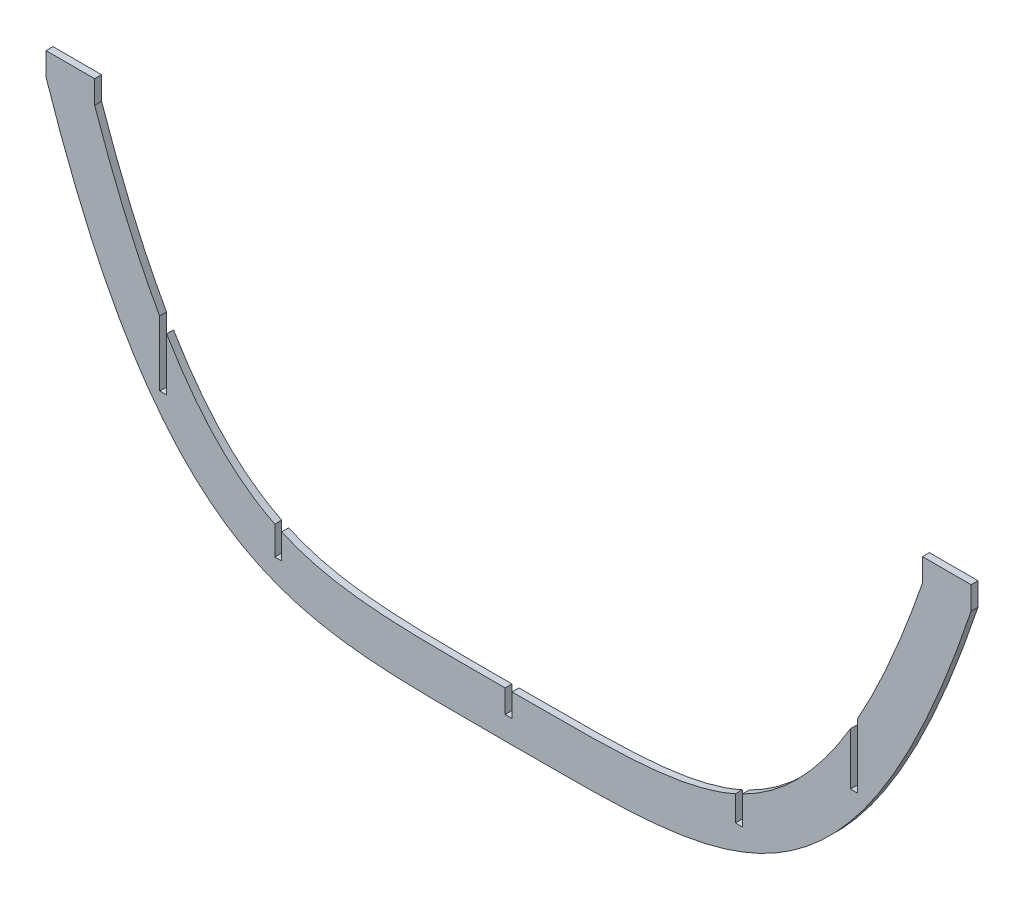
SolidWorks part; units mm, degrees
ref_plane "Front Plane" through (0, 0, 0) normal (0, 0, 1) x (1, 0, 0)
ref_plane "Top Plane" through (0, 0, 0) normal (0, 1, 0) x (1, 0, 0)
ref_plane "Right Plane" through (0, 0, 0) normal (1, 0, 0) x (0, 0, -1)
sketch "Sketch1" plane through (0, 0, 0) normal (0, 0, 1) x (1, 0, 0)
  line L4 (-200.8571, 150) -> (-200.8571, 160)
  line L5 (-200.8571, 160) -> (-179.7305, 160)
  line L6 (-179.7305, 160) -> (-179.7305, 150)
  line L7 (200.8571, 150) -> (200.8571, 160)
  line L8 (200.8571, 160) -> (179.7305, 160)
  line L9 (179.7305, 160) -> (179.7305, 150)
  spline S0 degree 4 poles (-216.8089, 203.6342) (-108.4044, -203.6342) (0, 203.6342) (108.4044, -203.6342) (216.8089, 203.6342) knots 0 0 0 0 0 1 1 1 1 1 construction
  spline S1 degree 4 poles (-200.8571, 150) (-100.4286, -150) (0, 150) (100.4286, -150) (200.8571, 150) knots 0.036788 0.036788 0.036788 0.036788 0.036788 0.963212 0.963212 0.963212 0.963212 0.963212
  spline S2 degree 1 poles (-181.8916, 156.3489) (181.8916, 156.3489) knots 0 0 1 1 construction
  spline S3 degree 3 poles (-181.8916, 156.3489) (-181.3891, 154.848) (-180.3653, 151.8253) (-178.3412, 145.9898) (-175.81, 138.9489) (-172.7858, 130.9351) (-168.7678, 120.7983) (-163.7768, 109.1306) (-157.8474, 96.6329) (-151.9892, 85.5414) (-144.2887, 72.4973) (-134.9007, 59.2193) (-124.0868, 47.3263) (-113.706, 38.6442) (-103.5943, 32.3808) (-93.4771, 27.8904) (-83.0914, 24.7263) (-68.685, 21.8783) (-49.5164, 20.3042) (-25.1066, 19.9753) (0, 20.0124) (25.1066, 19.9753) (49.5164, 20.3042) (68.685, 21.8783) (83.0914, 24.7263) (93.4771, 27.8904) (103.5943, 32.3808) (113.706, 38.6442) (124.0868, 47.3263) (134.9007, 59.2193) (144.2887, 72.4973) (151.9892, 85.5414) (157.8474, 96.6329) (163.7768, 109.1306) (168.7678, 120.7983) (172.7858, 130.9351) (175.81, 138.9489) (178.3412, 145.9898) (180.3653, 151.8253) (181.3891, 154.848) (181.8916, 156.3489) knots 0.036788 0.036788 0.036788 0.036788 0.040406 0.044025 0.051263 0.058501 0.065738 0.080214 0.094689 0.109165 0.12364 0.152591 0.181541 0.210492 0.239443 0.268394 0.297345 0.326295 0.384197 0.442098 0.5 0.557902 0.615803 0.673705 0.702655 0.731606 0.760557 0.789508 0.818459 0.847409 0.87636 0.890835 0.905311 0.919786 0.934262 0.941499 0.948737 0.955975 0.959594 0.963212 0.963212 0.963212 0.963212 only from (-179.7305, 150) to (179.7305, 150)
  dimension "D1" = 20
extrude "Boss-Extrude1" add sketch "Sketch1" along normal blind 3 contours S1 L7 L8 L9 S3 L6 L5 L4
sketch "Sketch2" plane through (0, 0, 0) normal (0, 0, 1) x (1, 0, 0)
  line L8 (1.5, 10) -> (-1.5, 10)
  line L12 (-1.5, 10) -> (-1.5, 21.3682)
  line L13 (-1.5, 21.3682) -> (1.5, 21.3682)
  line L14 (1.5, 10) -> (1.5, 21.3682)
extrude "Cut-Extrude2" cut sketch "Sketch2" along normal blind 22
sketch "Sketch4" plane through (0, 0, 0) normal (0, 0, 1) x (1, 0, 0)
  line L5 (101.5, 19.216) -> (98.5, 19.216)
  line L6 (101.5, 19.216) -> (101.5, 32.1285)
  line L7 (101.5, 32.1285) -> (98.5, 32.1285)
  line L8 (98.5, 19.216) -> (98.5, 32.1285)
extrude "Cut-Extrude3" cut sketch "Sketch4" along normal blind 45
sketch "Sketch5" plane through (0, 0, 0) normal (0, 0, 1) x (1, 0, 0)
  line L5 (-98.5, 19.216) -> (-101.5, 19.216)
  line L6 (-98.5, 19.216) -> (-98.5, 36.9515)
  line L7 (-98.5, 36.9515) -> (-101.5, 36.9515)
  line L8 (-101.5, 19.216) -> (-101.5, 36.9515)
extrude "Cut-Extrude4" cut sketch "Sketch5" along normal blind 38
sketch "Sketch6" plane through (0, 0, 0) normal (0, 0, 1) x (1, 0, 0)
  line L6 (-148.5, 56.656) -> (-151.5, 56.656)
  line L7 (-148.5, 56.656) -> (-148.5, 87.4942)
  line L8 (-148.5, 87.4942) -> (-151.5, 87.4942)
  line L9 (-151.5, 56.656) -> (-151.5, 87.4942)
extrude "Cut-Extrude5" cut sketch "Sketch6" along normal blind 99
sketch "Sketch7" plane through (0, 0, 0) normal (0, 0, 1) x (1, 0, 0)
  line L2 (148.5, 59.9497) -> (148.5, 86.6745)
  line L3 (148.5, 59.9497) -> (148.5, 56.9497)
  line L4 (148.5, 56.9497) -> (151.5, 56.9497)
  line L5 (151.5, 56.9497) -> (151.5, 59.9497)
  line L7 (151.5, 59.9497) -> (151.5, 86.6745)
  line L8 (151.5, 86.6745) -> (148.5, 86.6745)
extrude "Cut-Extrude6" cut sketch "Sketch7" along normal blind 239
